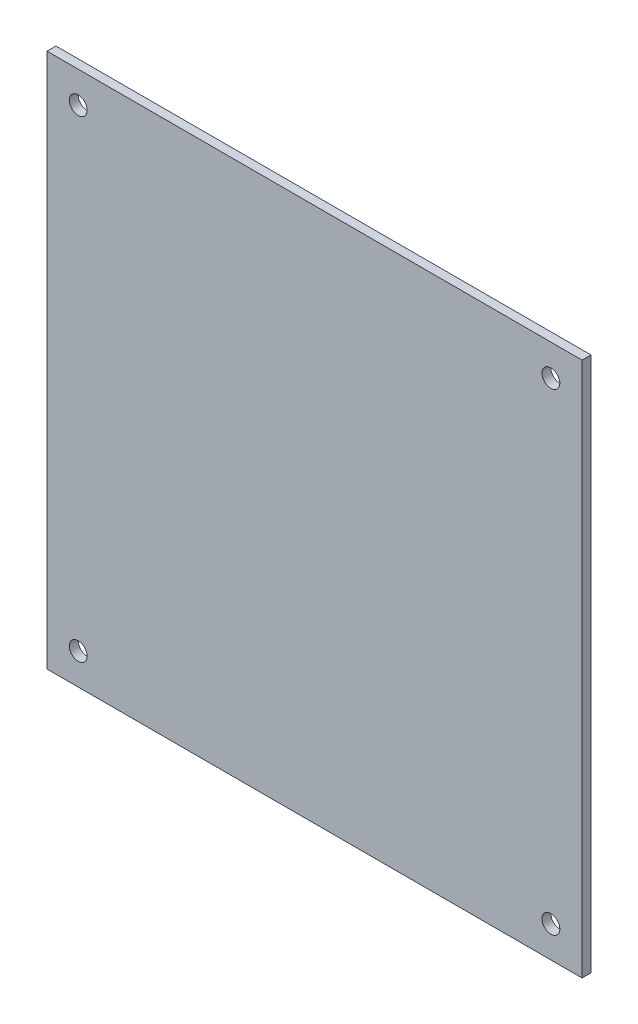
SolidWorks part; units mm, degrees
material "ASTM A36 Steel"
ref_plane "Front Plane" through (0, 0, 0) normal (0, 0, 1) x (1, 0, 0)
ref_plane "Top Plane" through (0, 0, 0) normal (0, 1, 0) x (1, 0, 0)
ref_plane "Right Plane" through (0, 0, 0) normal (1, 0, 0) x (0, 0, -1)
sketch "Sketch1" plane through (0, 0, 0) normal (0, 0, 1) x (1, 0, 0)
  line L1 (137.455, 81.0135) -> (-162.545, 81.0135)
  line L2 (137.455, 81.0135) -> (137.455, -218.9865)
  line L3 (137.455, -218.9865) -> (-162.545, -218.9865)
  line L4 (-162.545, 81.0135) -> (-162.545, -218.9865)
  circle A0 centre (-145.045, 63.5135) radius 5
  circle A1 centre (119.955, 63.5135) radius 5
  circle A2 centre (119.955, -201.4865) radius 5
  circle A3 centre (-145.045, -201.4865) radius 5
  dimension "D7" = 10
  dimension "D8" = 10
  dimension "D9" = 10
  dimension "D1" = 300
  dimension "D2" = 300
  dimension "D3" = 265
  dimension "D4" = 265
extrude "Boss-Extrude1" add sketch "Sketch1" along normal blind 5
